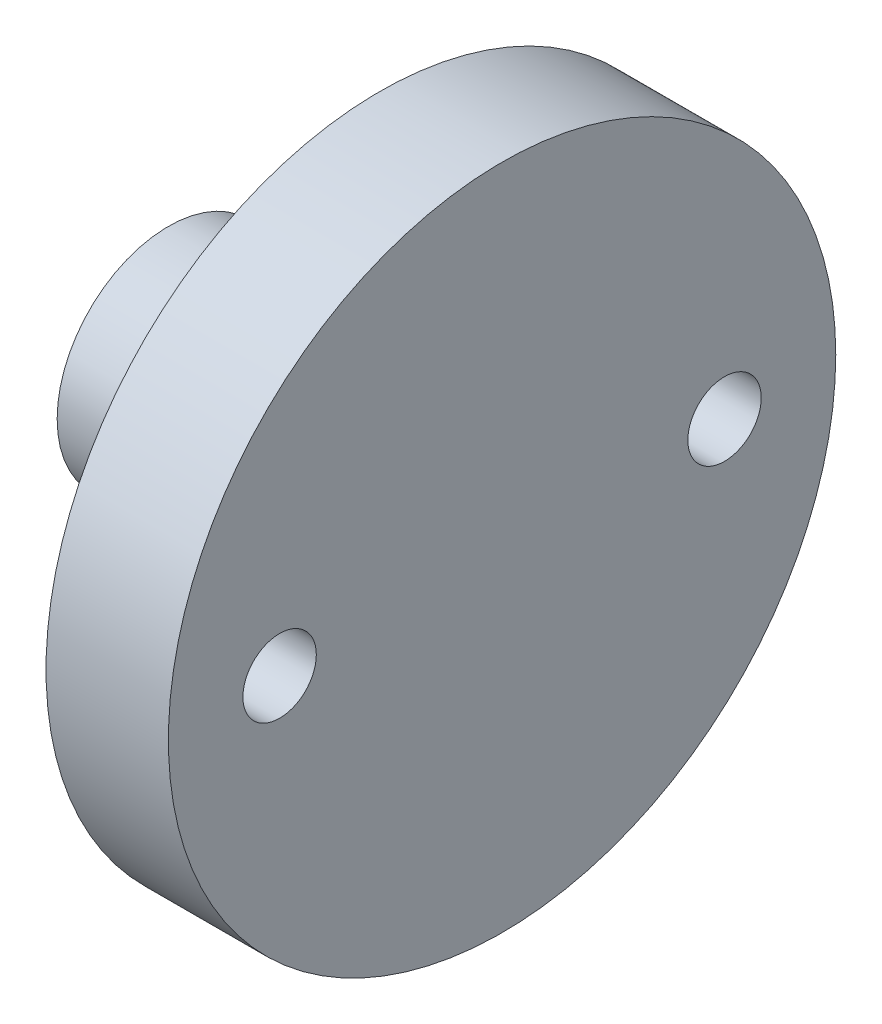
SolidWorks part; units mm, degrees
material "1060 合金"
ref_plane "正面" through (0, 0, 0) normal (0, 0, 1) x (1, 0, 0)
ref_plane "平面" through (0, 0, 0) normal (0, 1, 0) x (1, 0, 0)
ref_plane "右側面" through (0, 0, 0) normal (1, 0, 0) x (0, 0, -1)
sketch "ｽｹｯﾁ1" plane through (0, 0, 0) normal (1, 0, 0) x (0, 0, -1)
  circle A0 centre (0, 0) radius 15
  dimension "D1" = 30
extrude "ﾎﾞｽ - 押し出し1" add sketch "ｽｹｯﾁ1" along normal blind 5.5
sketch "ｽｹｯﾁ2" plane through (0, 0, 0) normal (-1, 0, 0) x (0, 0, 1)
  circle A0 centre (0, 0) radius 6
  dimension "D1" = 12
extrude "ﾎﾞｽ - 押し出し2" add sketch "ｽｹｯﾁ2" along normal blind 2
sketch "ｽｹｯﾁ3" plane through (-2, 0, 0) normal (-1, 0, 0) x (0, 0, 1)
  circle A0 centre (0, 0) radius 5
  dimension "D1" = 10
extrude "ﾎﾞｽ - 押し出し3" add sketch "ｽｹｯﾁ3" along normal blind 7.5
sketch "ｽｹｯﾁ4" plane through (5.5, 0, 0) normal (1, 0, 0) x (0, 0, -1)
  line L0 (0, 0) -> (0, 50000) construction
  line L1 (0, 0) -> (50000, 0) construction
  circle A0 centre (10, 0) radius 1.65
  circle A1 centre (-10, 0) radius 1.65
  dimension "D1" = 20
  dimension "D2" = 3.3
extrude "ｶｯﾄ - 押し出し1" cut sketch "ｽｹｯﾁ4" against normal through all
